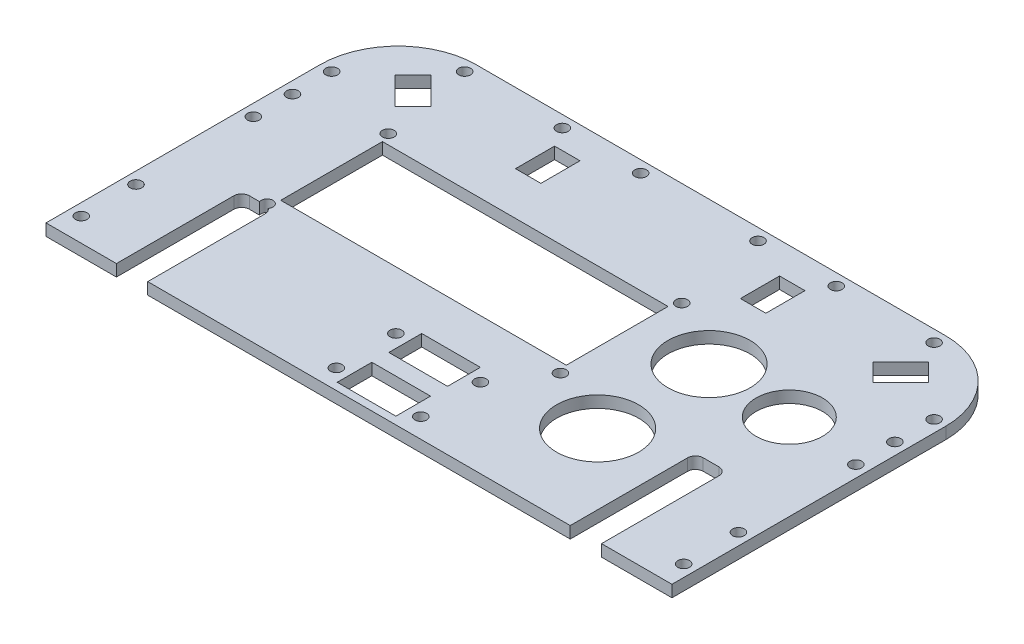
SolidWorks part; units mm, degrees
ref_plane "Alzado" through (0, 0, 0) normal (0, 0, 1) x (1, 0, 0)
ref_plane "Planta" through (0, 0, 0) normal (0, 1, 0) x (1, 0, 0)
ref_plane "Vista lateral" through (0, 0, 0) normal (1, 0, 0) x (0, 0, -1)
sketch "Croquis1" plane through (0, 0, 0) normal (0, 1, 0) x (1, 0, 0)
  line L0 (-98.5, -9.1729) -> (-98.5, -59.6432) construction
  line L1 (-20, 0) -> (-140, 0)
  line L2 (0, -20) -> (0, -90)
  line L3 (0, -90) -> (-160, -90)
  line L4 (-160, -20) -> (-160, -90)
  line L5 (-135, -55) -> (-62, -55)
  line L6 (-135, -55) -> (-135, -29)
  line L7 (-135, -29) -> (-62, -29)
  line L8 (-62, -55) -> (-62, -29)
  line L9 (-140, -42) -> (-42.9169, -42) construction
  line L10 (-80, 7.6599) -> (-80, -95.8532) construction
  line L11 (-148.1673, -12.5962) -> (-143.5711, -8)
  line L12 (-54.5, -8) -> (-48, -8)
  line L13 (-54.5, -8) -> (-54.5, -18)
  line L14 (-54.5, -18) -> (-48, -18)
  line L15 (-48, -8) -> (-48, -18)
  line L16 (-112, -8) -> (-105.5, -8)
  line L17 (-112, -8) -> (-112, -18)
  line L18 (-112, -18) -> (-105.5, -18)
  line L19 (-105.5, -8) -> (-105.5, -18)
  line L20 (-143.5711, -8) -> (-136.5, -15.0711)
  line L21 (-136.5, -15.0711) -> (-141.0962, -19.6673)
  line L22 (-141.0962, -19.6673) -> (-148.1673, -12.5962)
  line L23 (-16.4289, -8) -> (-11.8327, -12.5962)
  line L24 (-11.8327, -12.5962) -> (-18.9038, -19.6673)
  line L25 (-18.9038, -19.6673) -> (-23.5, -15.0711)
  line L26 (-23.5, -15.0711) -> (-16.4289, -8)
  arc A0 (-20, 0) -> (0, -20) centre (-20, -20) cw
  arc A1 (-140, 0) -> (-160, -20) centre (-140, -20) ccw
  circle A2 centre (-61, -26.5) radius 1.5
  circle A3 centre (-61, -57.5) radius 1.5
  circle A4 centre (-136, -57.5) radius 1.5
  circle A5 centre (-136, -26.5) radius 1.5
  circle A6 centre (-44, -65) radius 10.5
  circle A7 centre (-44, -36.5165) radius 10.5
  circle A8 centre (-22, -38) radius 8.5
  circle A9 centre (-90.795, -69.76) radius 1.5
  circle A10 centre (-69.205, -69.76) radius 1.5
  circle A11 centre (-69.205, -85) radius 1.5
  circle A12 centre (-90.795, -85) radius 1.5
  point P7 (0, 0)
  point P10 (-160, 0)
  point P59 (-140.0355, -11.5355)
  point P60 (0, 0)
  point P61 (0, 0)
  point P62 (-26.1815, -68.0074)
  point P63 (-48.5, -36.5165)
  point P64 (0, 0)
  dimension "D3" = 20
  dimension "D6" = 3
  dimension "D11" = 21
  dimension "D15" = 17
  dimension "D18" = 3
  dimension "D21" = 5
  dimension "D1" = 160
  dimension "D2" = 90
  dimension "D4" = 73
  dimension "D5" = 26
  dimension "D7" = 31
  dimension "D8" = 75
  dimension "D9" = 48
  dimension "D10" = 25
  dimension "D13" = 65
  dimension "D14" = 116
  dimension "D16" = 52
  dimension "D17" = 22
  dimension "D19" = 15.24
  dimension "D20" = 21.59
  dimension "D22" = 6.5
  dimension "D23" = 10
  dimension "D24" = 10
  dimension "D25" = 6.5
  dimension "D26" = 48
  dimension "D27" = 135
  dimension "D28" = 8
  dimension "D29" = 24.5
extrude "Saliente-Extruir2" add sketch "Croquis1" along normal blind 3
sketch "Croquis2" plane through (0, 3, 0) normal (0, 1, 0) x (1, 0, 0)
  line L0 (-160, -90) -> (0, -90) construction
  line L1 (-142, -90) -> (-134, -90)
  line L2 (-142, -90) -> (-142, -60)
  line L3 (-140, -58) -> (-136, -58)
  line L4 (-134, -90) -> (-134, -60)
  line L5 (-80, 11.8959) -> (-80, -119.3844) construction
  line L6 (-26, -90) -> (-18, -90)
  line L7 (-26, -90) -> (-26, -60)
  line L8 (-24, -58) -> (-20, -58)
  line L9 (-18, -90) -> (-18, -60)
  line L10 (0, -90) -> (0, -20) construction
  line L11 (-160, -20) -> (-160, -90) construction
  arc A0 (-136, -58) -> (-134, -60) centre (-136, -60) cw
  arc A1 (-142, -60) -> (-140, -58) centre (-140, -60) cw
  arc A2 (-20, -58) -> (-18, -60) centre (-20, -60) cw
  arc A3 (-26, -60) -> (-24, -58) centre (-24, -60) cw
  point P20 (-142, -58)
  dimension "D4" = 2
  dimension "D5" = 2
  dimension "D6" = 2
  dimension "D7" = 2
  dimension "D1" = 8
  dimension "D2" = 108
  dimension "D3" = 32
extrude "Cortar-Extruir1" cut sketch "Croquis2" against normal blind 10
sketch "Croquis3" plane through (0, 3, 0) normal (0, 1, 0) x (1, 0, 0)
  line L0 (-80, 9.4696) -> (-80, -108.4182) construction
  line L1 (0, -90) -> (0, -20) construction
  line L2 (-160, -20) -> (-160, -90) construction
  line L3 (-134, -90) -> (-26, -90) construction
  line L4 (-20, 0) -> (-140, 0) construction
  circle A0 centre (-157, -84) radius 1.5
  circle A1 centre (-157, -70) radius 1.5
  circle A2 centre (-157, -40) radius 1.5
  circle A3 centre (-157, -30) radius 1.5
  circle A4 centre (-140, -3) radius 1.5
  circle A5 centre (-115, -3) radius 1.5
  circle A6 centre (-95, -3) radius 1.5
  circle A7 centre (-65, -3) radius 1.5
  circle A8 centre (-45, -3) radius 1.5
  circle A9 centre (-20, -3) radius 1.5
  circle A10 centre (-3, -30) radius 1.5
  circle A11 centre (-3, -40) radius 1.5
  circle A12 centre (-3, -70) radius 1.5
  circle A13 centre (-3, -84) radius 1.5
  circle A14 centre (-157, -20) radius 1.5
  circle A15 centre (-3, -20) radius 1.5
  point P38 (0, 0)
  point P39 (0, 0)
  dimension "D1" = 3
  dimension "D2" = 15
  dimension "D3" = 35
  dimension "D4" = 60
  dimension "D5" = 6
  dimension "D6" = 20
  dimension "D7" = 50
  dimension "D8" = 60
  dimension "D9" = 10
  dimension "D10" = 3
  dimension "D11" = 3
extrude "Cortar-Extruir2" cut sketch "Croquis3" against normal blind 10
sketch "Croquis4" plane through (0, 3, 0) normal (0, 1, 0) x (1, 0, 0)
  line L0 (-80, -59.6305) -> (-80, -95.544) construction
  line L1 (-87.5, -66.4623) -> (-72.5, -66.4623)
  line L2 (-87.5, -66.4623) -> (-87.5, -74.8637)
  line L3 (-87.5, -74.8637) -> (-72.5, -74.8637)
  line L4 (-72.5, -66.4623) -> (-72.5, -74.8637)
  line L5 (-87.5, -79.2029) -> (-72.5, -79.2029)
  line L6 (-87.5, -79.2029) -> (-87.5, -88.0659)
  line L7 (-87.5, -88.0659) -> (-72.5, -88.0659)
  line L8 (-72.5, -79.2029) -> (-72.5, -88.0659)
  circle A0 centre (-69.205, -69.76) radius 1.5 construction
  circle A1 centre (-90.795, -69.76) radius 1.5 construction
  circle A2 centre (-69.205, -85) radius 1.5 construction
  circle A3 centre (-90.795, -85) radius 1.5 construction
  dimension "D1" = 15
  dimension "D2" = 15
extrude "Cortar-Extruir3" cut sketch "Croquis4" against normal blind 10
